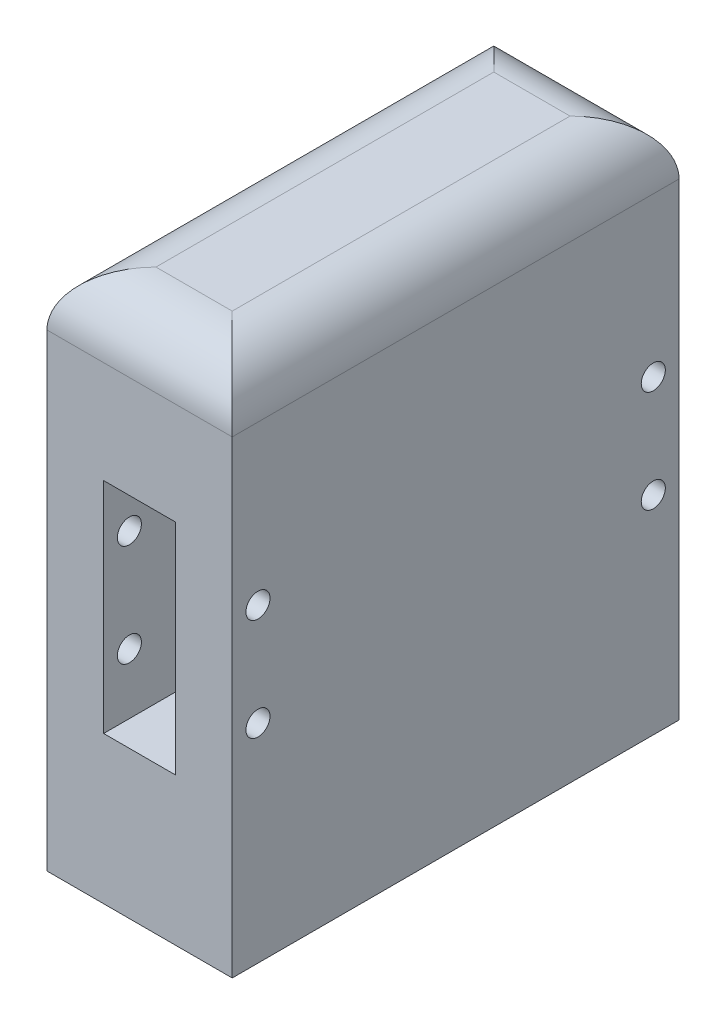
SolidWorks part; units mm, degrees
ref_plane "Front Plane" through (0, 0, 0) normal (0, 0, 1) x (1, 0, 0)
ref_plane "Top Plane" through (0, 0, 0) normal (0, 1, 0) x (1, 0, 0)
ref_plane "Right Plane" through (0, 0, 0) normal (1, 0, 0) x (0, 0, -1)
sketch "Sketch1" plane through (0, 0, 0) normal (0, 1, 0) x (1, 0, 0)
  line L1 (-8.5, -20.5) -> (8.5, -20.5)
  line L2 (-8.5, -20.5) -> (-8.5, 20.5)
  line L3 (-8.5, 20.5) -> (8.5, 20.5)
  line L4 (8.5, -20.5) -> (8.5, 20.5)
  line L5 (-8.5, -20.5) -> (8.5, 20.5) construction
  line L6 (-8.5, 20.5) -> (8.5, -20.5) construction
  point P0 (0, 0)
  dimension "D1" = 17
  dimension "D2" = 41
extrude "Boss-Extrude1" add sketch "Sketch1" along normal blind 48
sketch "Sketch2" plane through (0, 0, -20.5) normal (0, 0, -1) x (-1, 0, 0)
  line L0 (-8.5, 0) -> (8.5, 0) construction
  line L1 (-3.3, 13.5324) -> (3.3, 13.5324)
  line L2 (-3.3, 13.5324) -> (-3.3, 33.6324)
  line L3 (-3.3, 33.6324) -> (3.3, 33.6324)
  line L4 (3.3, 13.5324) -> (3.3, 33.6324)
  line L5 (-3.3, 13.5324) -> (3.3, 33.6324) construction
  line L6 (-3.3, 33.6324) -> (3.3, 13.5324) construction
  point P0 (0, 23.5824)
  dimension "D1" = 6.6
  dimension "D2" = 20.1
  dimension "D3" = 13.5324
  dimension "D4" = 3.3
extrude "Cut-Extrude1" cut sketch "Sketch2" against normal through all
sketch "Sketch3" plane through (8.5, 0, 0) normal (1, 0, 0) x (0, 0, -1)
  line L0 (-20.5, 48) -> (-20.5, 0) construction
  line L1 (-20.5, 13.5324) -> (-20.5, 33.6324) construction
  line L2 (-20.5, 0) -> (20.5, 0) construction
  line L3 (0, 0) -> (0, 52.4011) construction
  circle A0 centre (-18.138, 19.0753) radius 1.105
  circle A1 centre (-18.138, 28.4553) radius 1.105
  circle A2 centre (18.138, 28.4553) radius 1.105
  circle A3 centre (18.138, 19.0753) radius 1.105
  dimension "D1" = 2.21
  dimension "D2" = 2.21
  dimension "D3" = 2.362
  dimension "D4" = 2.362
  dimension "D5" = 9.38
  dimension "D6" = 19.0753
extrude "Cut-Extrude2" cut sketch "Sketch3" against normal through all
sketch "Sketch4" plane through (0, 0, 0) normal (0, -1, 0) x (1, 0, 0)
  circle A0 centre (0, 0) radius 6.4
  dimension "D1" = 12.8
extrude "Cut-Extrude3" cut sketch "Sketch4" against normal blind 42
fillet "Fillet3" radius 5 4 edges at (0, 48, 20.5) (-8.5, 48, 0) (0, 48, -20.5) (8.5, 48, 0)
sketch "Sketch8" plane through (0, 42, 0) normal (0, -1, 0) x (1, 0, 0)
  line L0 (8.5, -20.5) -> (8.5, 20.5) construction
  line L1 (-4, 13.6723) -> (4, 13.6723)
  line L2 (-4, 13.6723) -> (-4, -13.6723)
  line L3 (-4, -13.6723) -> (4, -13.6723)
  line L4 (4, 13.6723) -> (4, -13.6723)
  line L5 (-4, 13.6723) -> (4, -13.6723) construction
  line L6 (-4, -13.6723) -> (4, 13.6723) construction
  circle A0 centre (0, 0) radius 6.4 construction
  point P0 (0, 0)
  dimension "D1" = 4
  dimension "D2" = 13.6723
  dimension "D3" = 8.5
extrude "Cut-Extrude4" cut sketch "Sketch8" along normal blind 15
hole_wizard "Tap Drill for M3 Tap1" positions "3DSketch1" profile "Sketch10" hole size "M3" standard "ISO"
sketch3d "3DSketch1"
  line L1 (-8.5, 0, -20.5) -> (-8.5, 0, 20.5) construction
  point P0 (0, 0, -12)
  point P2 (0, 0, 12)
  dimension "D1" = 12
  dimension "D2" = 12
  dimension "D3" = 8.5
  dimension "D4" = 8.5
sketch "Sketch10" plane through (0, 0, -12) normal (1, 0, 0) x (0, 0, -1)
  line L0 (0, 0) -> (0, 14.2825)
  line L1 (0, 14.2825) -> (1.25, 13.5314)
  line L2 (1.25, 13.5314) -> (1.25, 0)
  line L5 (1.25, 0) -> (0, 0)
  line L10 (0, 14.2825) -> (-1.25, 13.5314) construction
  line L11 (0, -6.35) -> (0, 107.95) construction
  dimension "Hole Dia." = 2.5
  dimension "Hole Depth" = 13.5314
  dimension "Drill Angle" = 118
